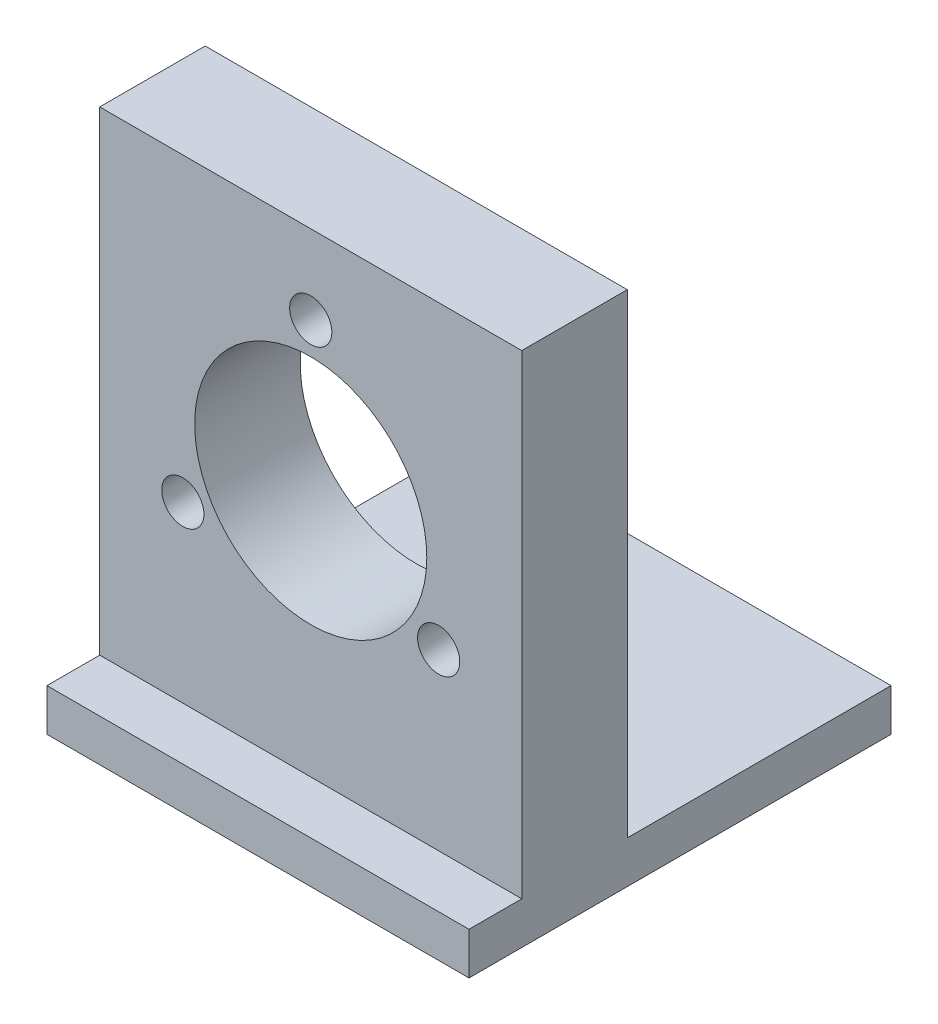
SolidWorks part; units mm, degrees
ref_plane "Front Plane" through (0, 0, 0) normal (0, 0, 1) x (1, 0, 0)
ref_plane "Top Plane" through (0, 0, 0) normal (0, 1, 0) x (1, 0, 0)
ref_plane "Right Plane" through (0, 0, 0) normal (1, 0, 0) x (0, 0, -1)
sketch "Sketch2" plane through (0, 0, 0) normal (0, 1, 0) x (1, 0, 0)
  line L1 (-12.2272, -14.2051) -> (27.7728, -14.2051)
  line L2 (-12.2272, -14.2051) -> (-12.2272, 25.7949)
  line L3 (-12.2272, 25.7949) -> (27.7728, 25.7949)
  line L4 (27.7728, -14.2051) -> (27.7728, 25.7949)
  dimension "D1" = 40
  dimension "D2" = 40
extrude "Boss-Extrude1" add sketch "Sketch2" along normal blind 4
sketch "Sketch3" plane through (0, 4, 0) normal (0, 1, 0) x (1, 0, 0)
  line L0 (-12.2272, 25.7949) -> (-12.2272, -14.2051) construction
  line L1 (-12.2272, 0.7949) -> (27.7728, 0.7949)
  line L2 (-12.2272, 0.7949) -> (-12.2272, -9.2051)
  line L3 (-12.2272, -9.2051) -> (27.7728, -9.2051)
  line L4 (27.7728, 0.7949) -> (27.7728, -9.2051)
  line L5 (27.7728, -14.2051) -> (27.7728, 25.7949) construction
  line L6 (-12.2272, -14.2051) -> (27.7728, -14.2051) construction
  dimension "D1" = 5
  dimension "D2" = 10
extrude "Boss-Extrude2" add sketch "Sketch3" along normal blind 45
sketch "Sketch4" plane through (0, 0, 9.2051) normal (0, 0, 1) x (1, 0, 0)
  line L0 (-12.2272, 49) -> (-12.2272, 4) construction
  line L1 (27.7728, 49) -> (27.7728, 4) construction
  line L2 (-12.2272, 4) -> (27.7728, 4) construction
  line L3 (-12.2272, 4) -> (27.7728, 4) construction
  circle A0 centre (7.7728, 27.5) radius 11
  circle A1 centre (19.8972, 20.5) radius 2
  circle A2 centre (-4.3515, 20.5) radius 2
  circle A3 centre (7.7728, 41.5) radius 2
  point P4 (27.7728, 26.5)
  point P19 (7.7728, 27.5)
  dimension "D4" = 22
  dimension "D5" = 4
  dimension "D1" = 20
  dimension "D2" = 20
  dimension "D3" = 23.5
  dimension "D6" = 14
  dimension "D8" = 16.5
  dimension "D7" = 3
extrude "Cut-Extrude1" cut sketch "Sketch4" against normal up to next
